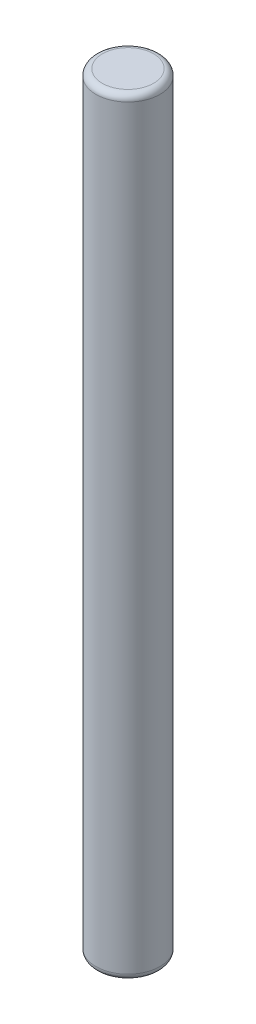
SolidWorks part; units mm, degrees
ref_plane "Front Plane" through (0, 0, 0) normal (0, 0, 1) x (1, 0, 0)
ref_plane "Top Plane" through (0, 0, 0) normal (0, 1, 0) x (1, 0, 0)
ref_plane "Right Plane" through (0, 0, 0) normal (1, 0, 0) x (0, 0, -1)
sketch "Sketch2" plane through (0, 0, 0) normal (0, 1, 0) x (1, 0, 0)
  circle A0 centre (0, 0) radius 1
  dimension "D1" = 2
extrude "Boss-Extrude1" add sketch "Sketch2" along normal blind 24
fillet "Fillet1" radius 0.2 2 edges at (0, 0, 1) (0, 24, 1)
